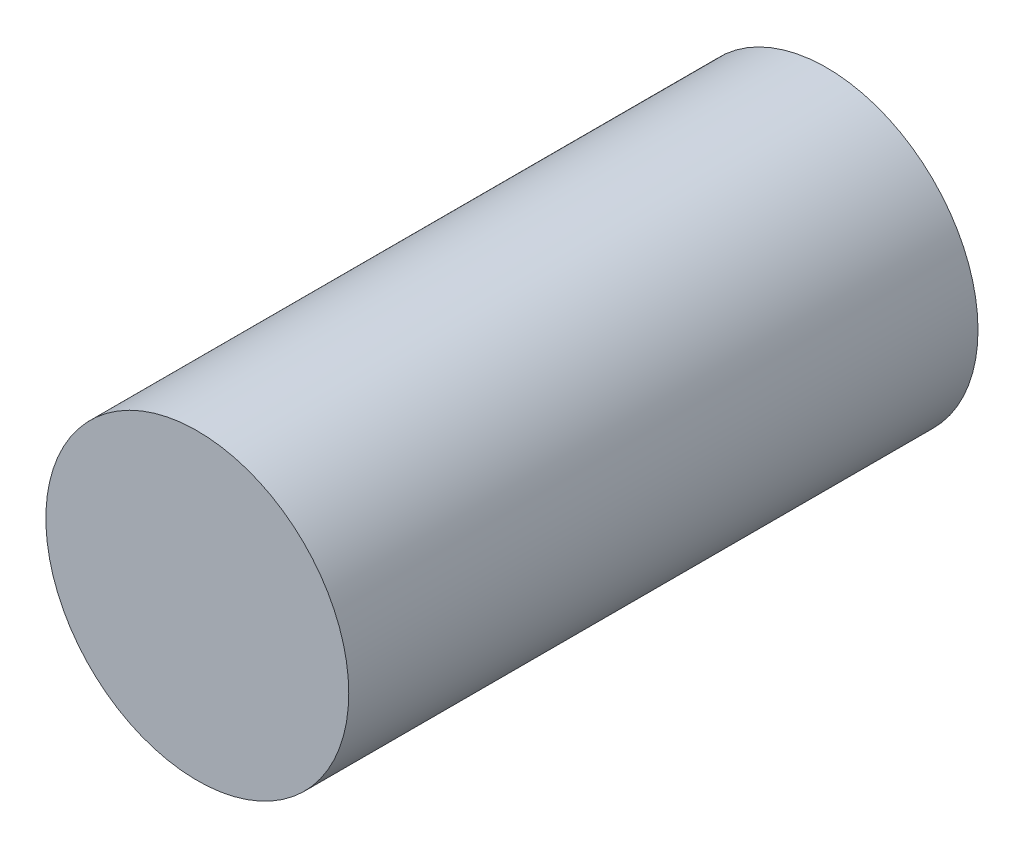
SolidWorks part; units mm, degrees
material "AISI Type A2 Tool Steel"
ref_plane "Front Plane" through (0, 0, 0) normal (0, 0, 1) x (1, 0, 0)
ref_plane "Top Plane" through (0, 0, 0) normal (0, 1, 0) x (1, 0, 0)
ref_plane "Right Plane" through (0, 0, 0) normal (1, 0, 0) x (0, 0, -1)
sketch "Sketch1" plane through (0, 0, 0) normal (0, 0, 1) x (1, 0, 0)
  circle A0 centre (0, 0) radius 6.0175
  dimension "D1" = 12.035
extrude "Boss-Extrude1" add sketch "Sketch1" along normal mid plane 25
